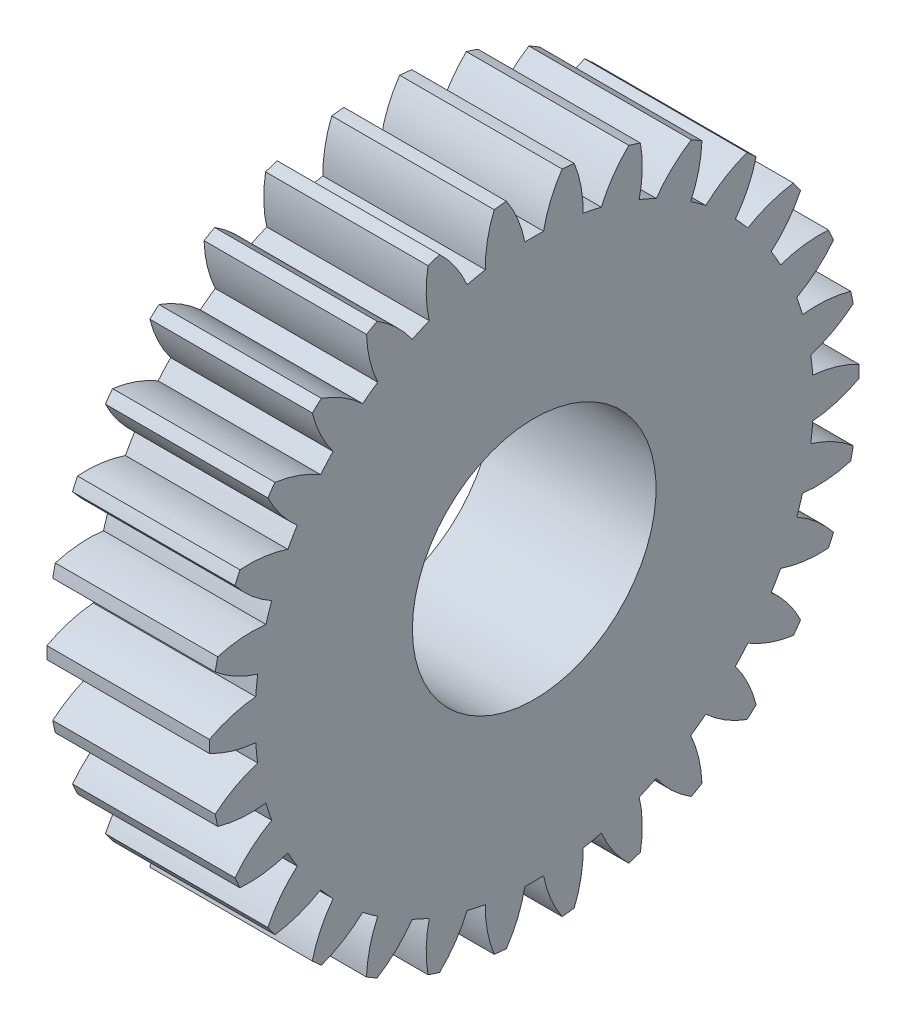
SolidWorks part; units mm, degrees
ref_plane "Plane1" through (0, 0, 0) normal (0, 0, 1) x (1, 0, 0)
ref_plane "Plane2" through (0, 0, 0) normal (0, 1, 0) x (1, 0, 0)
ref_plane "Plane3" through (0, 0, 0) normal (1, 0, 0) x (0, 0, -1)
sketch "HoldingSke" plane through (0, 0, 0) normal (0, 1, 0) x (1, 0, 0)
  line L0 (0, 0) -> (0.433, -0.25)
  line L1 (-15, 0) -> (100, 0) construction
  line L2 (0, 0) -> (-2.1039, 2.3779)
  line L3 (0, 0) -> (-11.863, 4.5341)
  line L4 (0, 0) -> (7.479, 4.318)
  line L5 (0, 0) -> (-46.8476, -17.4728)
  line L6 (0, 0) -> (-13.2634, -8.9489)
  line L7 (-2.1039, 2.3779) -> (8.6586, 51.2059)
  line L8 (-76.2, 54.61) -> (-72.9, 54.61)
  line L9 (-71.009, 38.7566) -> (-53.1078, 45.2721)
  line L10 (-76.2, 71.12) -> (104.1128, 71.12)
  line L11 (0, 0) -> (-16, 0)
  line L12 (-76.2, 101.6) -> (-76.133, 101.6)
  line L13 (24.9733, 27.94) -> (52.9518, 28.4284)
  line L14 (24.9733, 27.94) -> (24.9743, 27.94)
  line L15 (24.9733, 27.94) -> (100.4006, 29.5858)
  line L16 (-63.627, -2) -> (-12.827, -2)
  circle A0 centre (0, 0) radius 12
  circle A1 centre (0, 0) radius 27.499
  circle A2 centre (0, 0) radius 37.5
  circle A3 centre (0, 0) radius 12
  dimension "MHD" = 54.998
  dimension "Hub_dia" = 75
  dimension "Bore" = 24
  dimension "MBD" = 24
  dimension "Num_teeth" = 30
  dimension "Pitch" = 0.5
  dimension "Overall_len" = 50
  dimension "Show_teeth" = 30
  dimension "Thickness" = 16
  dimension "OAL" = 50.0001
  dimension "T_dim" = 3.3
  dimension "Ap" = 20
  dimension "H" = 19.05
  dimension "Pitch_radius" = 180.3128
  dimension "Width" = 16
  dimension "Backlash" = 0.067
  dimension "Addendum_fac" = 1
  dimension "Dedendum_fac" = 1.25
  dimension "Clearance_fac" = 0.25
  dimension "Dedendum_add" = 0.001
  dimension "Module" = 2
sketch "BasProSke" plane through (0, 0, 0) normal (0, 1, 0) x (1, 0, 0)
  line L0 (-10, 0) -> (60, 0) construction
  line L1 (0, 0) -> (0, 32)
  line L2 (0, 0) -> (16, 0)
  line L3 (16, 0) -> (16, 32)
  line L4 (16, 32) -> (0, 32)
  dimension "Thickness" = 16
  dimension "Diameter" = 64
revolve "Base-Revolve" add sketch "BasProSke" angle 360 about L0
sketch "TooCutSke" plane through (0, 0, 0) normal (1, 0, 0) x (0, 0, -1)
  line L1 (0, 0) -> (0, 107) construction
  line L2 (0, 0) -> (-1.6873, 29.9525) construction
  line L3 (0, 0) -> (-6.2643, 59.6013) construction
  line L4 (-1.6873, 29.9525) -> (-3.1322, 29.8007) construction
  arc A0 (0.9186, 27.4837) -> (-0.9186, 27.4837) centre (0, 0) ccw
  arc A1 (2.7618, 31.9061) -> (-2.7618, 31.9061) centre (0, 0) ccw
  circle A2 centre (0, 0) radius 30 construction
  circle A3 centre (0, 0) radius 28.1908 construction
  arc A4 (-0.9186, 27.4837) -> (-2.7618, 31.9061) centre (-12.6936, 25.1712) ccw
  arc A5 (2.7618, 31.9061) -> (0.9186, 27.4837) centre (12.6936, 25.1712) ccw
  dimension "Root_dia" = 54.998
  dimension "Overcut_dia" = 64.0508
  dimension "Pitch_dia" = 60
  dimension "Base_dia" = 56.3816
  dimension "Flank_rad" = 12
  dimension "Half_ang" = 6
  dimension "Half_CT" = 1.4528
extrude "ToothCut" cut sketch "TooCutSke" along normal through all
fillet "Breaks" [suppressed] radius 0.04
fillet "RootFillets" [suppressed] radius 0.501
pattern_circular "TeethCuts" count 30 every 12 about axis through (-10, 0, 0) along (1, 0, 0) of "ToothCut", "RootFillets", "Breaks"
sketch "HubNeaOneSke" plane through (0, 0, 0) normal (-1, 0, 0) x (0, 0, 1)
  circle A0 centre (0, 0) radius 27.499
  dimension "Diameter" = 54.998
extrude "HubNearOne" [suppressed] add sketch "HubNeaOneSke" along normal blind 34.0001
sketch "HubNeaBotSke" plane through (0, 0, 0) normal (-1, 0, 0) x (0, 0, 1)
  circle A0 centre (0, 0) radius 27.499
  dimension "Diameter" = 54.998
extrude "HubNearBoth" [suppressed] add sketch "HubNeaBotSke" along normal blind 17
ref_plane "FarPln" through (16, 0, 0) normal (1, 0, 0) x (0, 0, -1)
sketch "HubFarSke" plane through (16, 0, 0) normal (1, 0, 0) x (0, 0, -1)
  circle A0 centre (0, 0) radius 27.499
  dimension "Diameter" = 54.998
extrude "HubFar" [suppressed] add sketch "HubFarSke" along normal blind 17
sketch "BorSke" plane through (0, 0, 0) normal (1, 0, 0) x (0, 0, -1)
  circle A0 centre (0, 0) radius 12
  dimension "Diameter" = 24
extrude "Bore" cut sketch "BorSke" along normal mid plane 100.0001
sketch "KeySke" plane through (0, 0, 0) normal (1, 0, 0) x (0, 0, -1)
  line L0 (-4, 0) -> (-4, 15.3)
  line L1 (-4, 15.3) -> (4, 15.3)
  line L2 (4, 15.3) -> (4, 0)
  line L3 (0, 0) -> (0, 34) construction
  line L4 (-4, 0) -> (4, 0)
  dimension "Offset" = 15.3
  dimension "Width" = 8
extrude "Keyway" [suppressed] cut sketch "KeySke" along normal mid plane 100.0001
pattern_circular "Keyway2" [suppressed] count 2 every 90 about axis through (-10, 0, 0) along (1, 0, 0)
equation "' \"Module@HoldingSke\" = 6.35"
equation "' \"Num_teeth@HoldingSke\" = 12"
equation "' \"Ap@HoldingSke\" =  20"
equation "' \"Ap@HoldingSke\" = 20"
equation "' \"Width@HoldingSke\" = 0.5 * 25.4"
equation "' \"Hub_dia@HoldingSke\"= 1 * 25.4"
equation "' \"Hub_dia@HoldingSke\" = 1 * 25.4"
equation "' \"Overall_len@HoldingSke\" = 1.0 * 25.4"
equation "' \"Bore@HoldingSke\" = 0.75 * 25.4"
equation "' \"T_dim@HoldingSke\" = 0.1 * 25.4"
equation "' \"Width@KeySke\" = 0.25 * 25.4"
equation "' \"Show_teeth@HoldingSke\" = 13"
equation "' \"Backlash@HoldingSke\" = 0.009 * 25.4"
equation "' \"Addendum_fac@HoldingSke\" = 1.0"
equation "' \"Dedendum_fac@HoldingSke\" = 1.25"
equation "' \"Dedendum_add@HoldingSke\" = 0.00005 * 25.4"
equation "' \"Clearance_fac@HoldingSke\" = 0.25"
equation "\"Pitch@HoldingSke\" = 1 / \"Module@HoldingSke\""
equation "\"Overcut_dia@TooCutSke\" = (\"Num_teeth@HoldingSke\" + 2 * \"Addendum_fac@HoldingSke\") / \"Pitch@HoldingSke\" + 0.002 * 25.4"
equation "\"Pitch_dia@TooCutSke\" = \"Num_teeth@HoldingSke\" / \"Pitch@HoldingSke\""
equation "\"Base_dia@TooCutSke\" = \"Num_teeth@HoldingSke\" / \"Pitch@HoldingSke\" * cos((\"Ap@HoldingSke\"  * 3.14159265 / 180))"
equation "\"Root_dia@TooCutSke\" = (\"Num_teeth@HoldingSke\" + 2) / \"Pitch@HoldingSke\" - 2 * (\"Addendum_fac@HoldingSke\" + \"Dedendum_fac@HoldingSke\") / \"Pitch@HoldingSke\" - \"Dedendum_add@HoldingSke\" * 2"
equation "\"Half_ang@TooCutSke\" = 180 / \"Num_teeth@HoldingSke\""
equation "\"Half_CT@TooCutSke\" = \"Num_teeth@HoldingSke\" / \"Pitch@HoldingSke\" * sin((3.14159265 / 2 / \"Num_teeth@HoldingSke\")) / 2 - 7 * \"Backlash@HoldingSke\" / 4"
equation "\"Flank_rad@TooCutSke\" = \"Num_teeth@HoldingSke\" / \"Pitch@HoldingSke\" / 5"
equation "\"Radius@RootFillets\" = \"Clearance_fac@HoldingSke\" / \"Pitch@HoldingSke\" + \"Dedendum_add@HoldingSke\""
equation "\"Break_rad@Breaks\" = 0.02 / \"Pitch@HoldingSke\""
equation "\"Thickness@HoldingSke\" = \"Width@HoldingSke\""
equation "\"OAL@HoldingSke\" = \"Thickness@HoldingSke\""
equation "\"MHD@HoldingSke\" = (\"Num_teeth@HoldingSke\" + 2) / \"Pitch@HoldingSke\" - 2 * (\"Addendum_fac@HoldingSke\" + \"Dedendum_fac@HoldingSke\")  / \"Pitch@HoldingSke\" - \"Dedendum_add@HoldingSke\" * 2"
equation "\"MBD@HoldingSke\" = (\"Num_teeth@HoldingSke\" + 2) / \"Pitch@HoldingSke\" - 2 * (\"Addendum_fac@HoldingSke\" + \"Dedendum_fac@HoldingSke\")  / \"Pitch@HoldingSke\" - \"Dedendum_add@HoldingSke\" * 2 - 0.002 * 25.4"
equation "\"MHD@HoldingSke\" = ((sgn( \"MHD@HoldingSke\" - \"Hub_dia@HoldingSke\" )-1)*( \"MHD@HoldingSke\" - \"Hub_dia@HoldingSke\" ))/-2+ \"Hub_dia@HoldingSke\""
equation "\"MBD@HoldingSke\" = ((sgn( \"MBD@HoldingSke\" - \"Bore@HoldingSke\" )-1)*( \"MBD@HoldingSke\" - \"Bore@HoldingSke\" ))/-2+ \"Bore@HoldingSke\""
equation "\"OAL@HoldingSke\" = ((sgn( \"OAL@HoldingSke\" - \"Overall_len@HoldingSke\" )+1)*( \"OAL@HoldingSke\" - \"Overall_len@HoldingSke\" ))/2 + \"Overall_len@HoldingSke\" + 0.000002 * 25.4"
equation "\"Num_teeth@TeethCuts\" = int( \"Show_teeth@HoldingSke\" ) + 1"
equation "\"Num_teeth@TeethCuts\" = ((sgn( \"Num_teeth@TeethCuts\" - \"Num_teeth@HoldingSke\" )-1)*( \"Num_teeth@TeethCuts\" - \"Num_teeth@HoldingSke\" ))/-2+ \"Num_teeth@HoldingSke\""
equation "\"Num_teeth@TeethCuts\" = ((sgn( \"Num_teeth@TeethCuts\" - 2.0)+1)*( \"Num_teeth@TeethCuts\" - 2.0))/2 +2.0"
equation "\"Angle@TeethCuts\" = 360.0 / \"Num_teeth@HoldingSke\""
equation "\"Diameter@BasProSke\" = (\"Num_teeth@HoldingSke\" + 2 * \"Addendum_fac@HoldingSke\") / \"Pitch@HoldingSke\""
equation "\"Thickness@BasProSke\"  = \"Thickness@HoldingSke\""
equation "' \"Fillet_rad@BasProSke\" =  \"Thickness@HoldingSke\" * 0.05"
equation "' \"Fillet_rad@BasProSke\" = \"Thickness@HoldingSke\" * 0.05"
equation "\"MHD@HoldingSke\" = ((sgn( \"MHD@HoldingSke\" - \"Root_dia@TooCutSke\" )-1)*( \"MHD@HoldingSke\" - \"Root_dia@TooCutSke\" ))/-2+ \"Root_dia@TooCutSke\""
equation "\"Diameter@HubNeaOneSke\" = \"MHD@HoldingSke\""
equation "\"Length@HubNearOne\" = \"OAL@HoldingSke\" - \"Thickness@BasProSke\""
equation "\"Diameter@HubNeaBotSke\" = \"MHD@HoldingSke\""
equation "\"Length@HubNearBoth\" = ( \"OAL@HoldingSke\" - \"Thickness@BasProSke\" ) / 2.0"
equation "\"Thickness@FarPln\" = \"Thickness@BasProSke\""
equation "\"Diameter@HubFarSke\" = \"MHD@HoldingSke\""
equation "\"Length@HubFar\" = ( \"OAL@HoldingSke\" - \"Thickness@BasProSke\" ) / 2.0"
equation "\"Diameter@BorSke\" = \"MBD@HoldingSke\""
equation "\"D1@Bore\" = \"OAL@HoldingSke\" * 2.0"
equation "\"D1@Keyway\" = \"OAL@HoldingSke\" * 2.0"
equation "\"Offset@KeySke\" = \"T_dim@HoldingSke\" + \"MBD@HoldingSke\" / 2.0"
